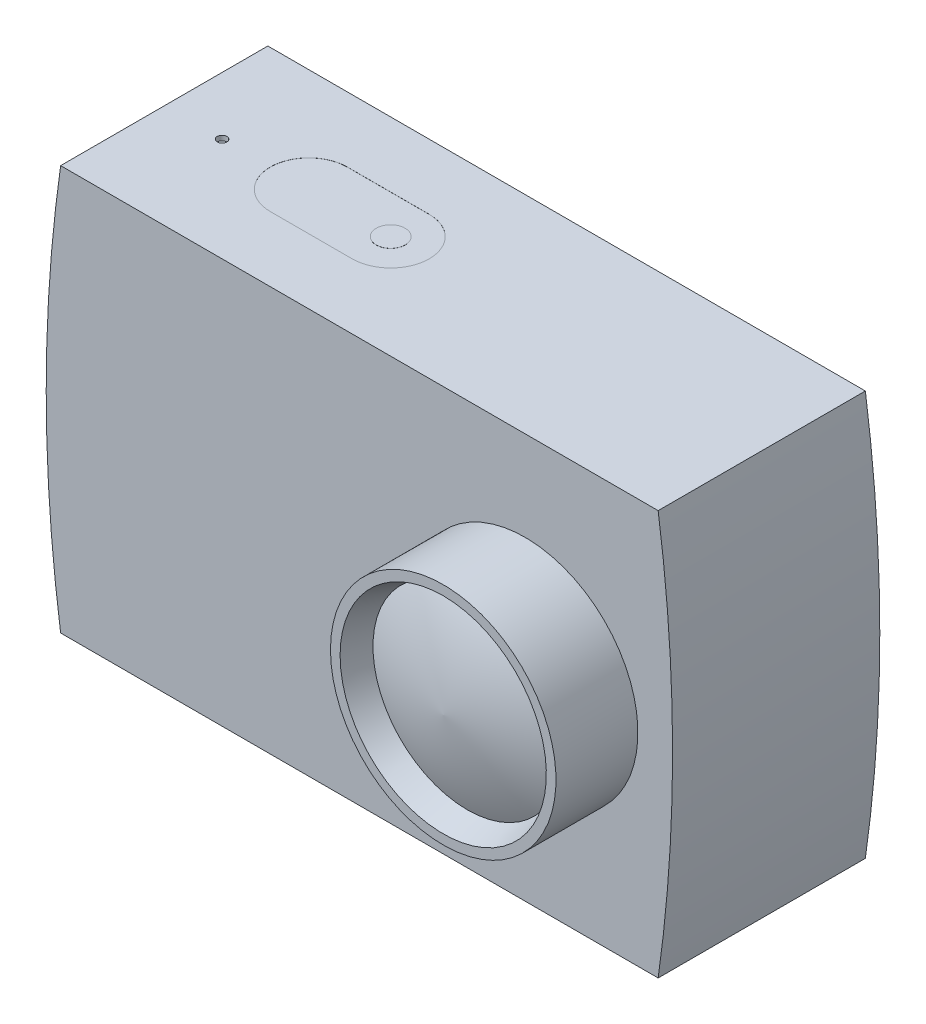
SolidWorks part; units mm, degrees
material "Yi 4K"
ref_plane "Alzado" through (0, 0, 0) normal (0, 0, 1) x (1, 0, 0)
ref_plane "Planta" through (0, 0, 0) normal (0, 1, 0) x (1, 0, 0)
ref_plane "Vista lateral" through (0, 0, 0) normal (1, 0, 0) x (0, 0, -1)
sketch "Croquis1" plane through (0, 0, 0) normal (0, 0, 1) x (1, 0, 0)
  line L0 (0, 0) -> (-62, 0)
  line L1 (-62, 42) -> (0, 42)
  line L2 (-62, 42) -> (-62, 0) construction
  line L3 (-62, 21) -> (-63.5, 21) construction
  line L4 (0, 42) -> (0, 21) construction
  line L5 (0, 21) -> (1.5, 21) construction
  arc A0 (-62, 42) -> (-62, 0) centre (84.5026, 21) ccw
  arc A1 (0, 42) -> (0, 0) centre (-146.5026, 21) cw
  dimension "D1" = 62
  dimension "D2" = 42
extrude "Saliente-Extruir1" add sketch "Croquis1" along normal blind 21.5
sketch "Croquis2" plane through (0, 42, 0) normal (0, 1, 0) x (1, 0, 0)
  line L1 (-51, -6.75) -> (-34.5, -6.75) construction
  line L2 (-51, -6.75) -> (-51, -14.75) construction
  line L3 (-51, -14.75) -> (-34.5, -14.75) construction
  line L4 (-34.5, -6.75) -> (-34.5, -14.75) construction
  line L5 (0, -21.5) -> (-62, -21.5) construction
  line L6 (-51, -10.75) -> (-47, -10.75) construction
  line L7 (-34.5, -10.75) -> (-38.5, -10.75) construction
  line L8 (-62, -21.5) -> (-62, 0) construction
  line L9 (-47, -6.75) -> (-38.5, -6.75)
  line L10 (-47, -14.75) -> (-38.5, -14.75)
  circle A0 centre (-47, -10.75) radius 4 construction
  circle A1 centre (-38.5, -10.75) radius 4 construction
  arc A2 (-47, -14.75) -> (-47, -6.75) centre (-47, -10.75) cw
  arc A3 (-38.5, -6.75) -> (-38.5, -14.75) centre (-38.5, -10.75) cw
  dimension "D1" = 11
  dimension "D2" = 16.5
  dimension "D3" = 6.75
  dimension "D4" = 4
  dimension "D5" = 4
extrude "Cortar-Extruir1" cut sketch "Croquis2" against normal blind 0.01
sketch "Croquis3" plane through (0, 41.99, 0) normal (0, 1, 0) x (1, 0, 0)
  circle A0 centre (-38.5, -10.75) radius 1.5
extrude "Saliente-Extruir2" add sketch "Croquis3" along normal blind 0.01
sketch "Croquis4" plane through (0, 42, 0) normal (0, 1, 0) x (1, 0, 0)
  line L0 (-62, -21.5) -> (-62, 0) construction
  circle A0 centre (-56, -10.75) radius 0.5
  dimension "D1" = 6
extrude "Cortar-Extruir2" cut sketch "Croquis4" against normal blind 0.5
sketch "Croquis5" plane through (0, 0, 21.5) normal (0, 0, 1) x (1, 0, 0)
  line L0 (1.4974, 21) -> (-25.5026, 21) construction
  line L1 (-25.5026, 21) -> (-13.8026, 21)
  arc A0 (0, 0) -> (0, 42) centre (-146.5026, 21) ccw construction
  dimension "D1" = 27
ref_plane "Plano1" through (0, 21, 0) normal (0, -1, 0) x (-1, 0, 0)
sketch "Croquis6" plane through (0, 21, 0) normal (0, -1, 0) x (-1, 0, 0)
  line L0 (25.5026, -21.5) -> (25.5026, -30)
  line L1 (25.5026, -30) -> (24.5026, -30)
  line L2 (24.5026, -30) -> (23.5926, -27.5)
  line L3 (13.8026, -21.5) -> (13.8026, -27.5)
  line L4 (23.5926, -27.5) -> (22.5926, -27.5)
  line L5 (25.5026, -21.5) -> (13.8026, -21.5)
  line L6 (22.5926, -27.5) -> (13.8026, -27.5)
  dimension "D1" = 1
  dimension "D2" = 8.5
  dimension "D3" = 1
  dimension "D4" = 110
  dimension "D5" = 6
revolve "Revolución1" add sketch "Croquis6" angle 360 about L3
sketch "Croquis8" plane through (0, 0, 27.5) normal (0, 0, 1) x (1, 0, 0)
  line L0 (-23.5926, 21) -> (-13.8026, 21)
  circle A0 centre (-13.8026, 21) radius 9.7901 construction
ref_plane "Plano2" through (0, 21, 0) normal (0, 1, 0) x (1, 0, 0)
sketch "Croquis9" plane through (0, 21, 0) normal (0, 1, 0) x (1, 0, 0)
  line L0 (-13.8026, -27.5) -> (-13.8026, -30)
  line L2 (-13.8026, -27.5) -> (-23.5926, -27.5)
  arc A0 (-23.5926, -27.5) -> (-13.8026, -30) centre (-11.8426, -1.9055) ccw
revolve "Revolución3" add sketch "Croquis9" angle 360 about L0
